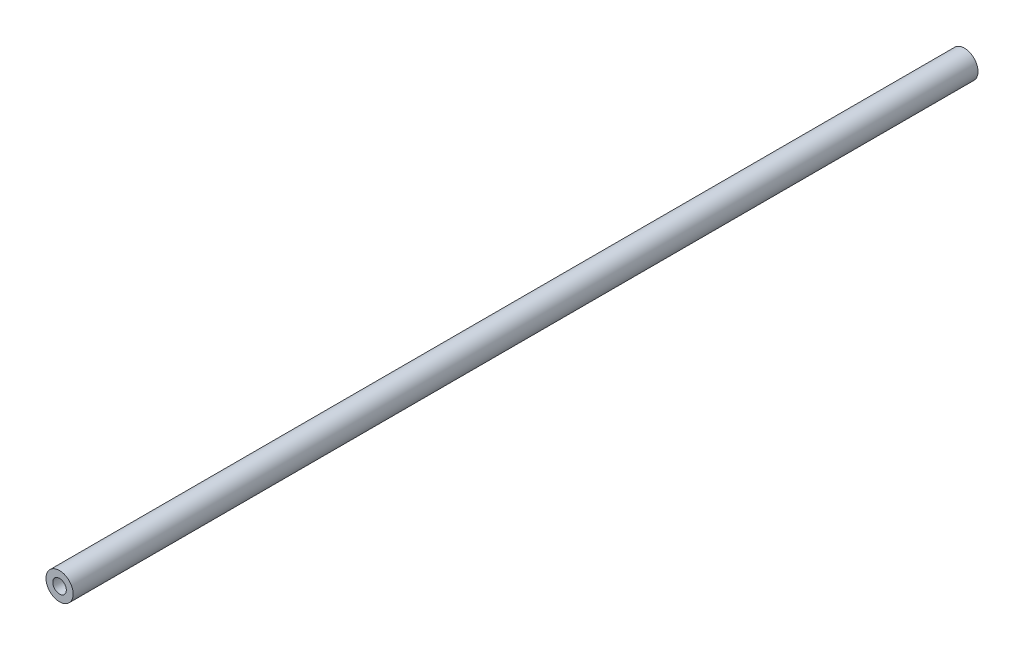
SolidWorks part; units mm, degrees
ref_plane "Front Plane" through (0, 0, 0) normal (0, 0, 1) x (1, 0, 0)
ref_plane "Top Plane" through (0, 0, 0) normal (0, 1, 0) x (1, 0, 0)
ref_plane "Right Plane" through (0, 0, 0) normal (1, 0, 0) x (0, 0, -1)
sketch "Sketch1" plane through (0, 0, 0) normal (0, 0, 1) x (1, 0, 0)
  circle A0 centre (0, 0) radius 3
  dimension "D1" = 6
extrude "Boss-Extrude1" add sketch "Sketch1" along normal mid plane 200
sketch "Sketch2" plane through (0, 0, 100) normal (0, 0, 1) x (1, 0, 0)
  circle A0 centre (0, 0) radius 1.5
  dimension "D1" = 3
extrude "Cut-Extrude1" cut sketch "Sketch2" against normal blind 10
mirror "Mirror1" about plane through (0, 0, 0) normal (0, 0, 1) of "Cut-Extrude1"
